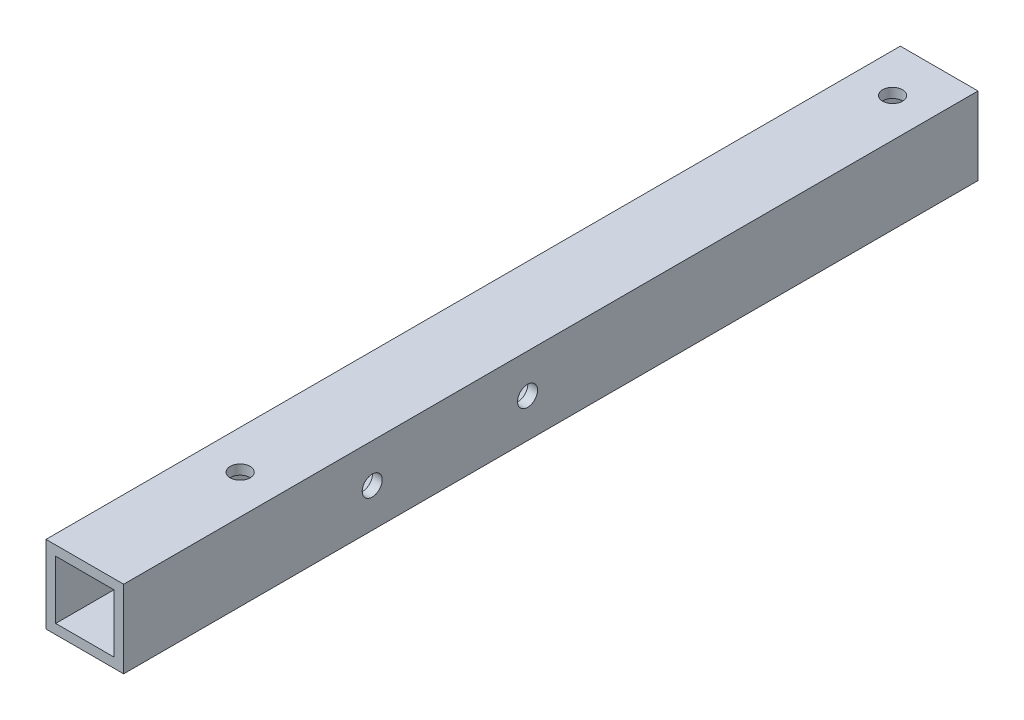
SolidWorks part; units mm, degrees
material "1060 Alloy"
ref_plane "Front Plane" through (0, 0, 0) normal (0, 0, 1) x (1, 0, 0)
ref_plane "Top Plane" through (0, 0, 0) normal (0, 1, 0) x (1, 0, 0)
ref_plane "Right Plane" through (0, 0, 0) normal (1, 0, 0) x (0, 0, -1)
sketch "Sketch2" plane through (0, 0, 0) normal (0, 0, 1) x (1, 0, 0)
  line L1 (12.7, -12.7) -> (-12.7, -12.7)
  line L2 (12.7, -12.7) -> (12.7, 12.7)
  line L3 (12.7, 12.7) -> (-12.7, 12.7)
  line L4 (-12.7, -12.7) -> (-12.7, 12.7)
  line L5 (12.7, -12.7) -> (-12.7, 12.7) construction
  line L6 (12.7, 12.7) -> (-12.7, -12.7) construction
  point P0 (0, 0)
  dimension "D1" = 25.4
extrude "Boss-Extrude1" add sketch "Sketch2" along normal blind 279.4 contours L4 L3 L2 L1
sketch "Sketch4" plane through (0, 0, 0) normal (0, 0, 1) x (1, 0, 0)
  line L0 (12.7, -12.7) -> (12.7, 12.7) construction
  line L1 (-9.525, -9.525) -> (9.525, -9.525)
  line L2 (-9.525, -9.525) -> (-9.525, 9.525)
  line L3 (-9.525, 9.525) -> (9.525, 9.525)
  line L4 (9.525, -9.525) -> (9.525, 9.525)
  line L5 (-9.525, -9.525) -> (9.525, 9.525) construction
  line L6 (-9.525, 9.525) -> (9.525, -9.525) construction
  line L7 (12.7, 12.7) -> (-12.7, 12.7) construction
  point P0 (0, 0)
  dimension "D1" = 3.175
  dimension "D2" = 3.175
extrude "Cut-Extrude1" cut sketch "Sketch4" along normal through all
sketch "Sketch5" plane through (0, 12.7, 0) normal (0, 1, 0) x (1, 0, 0)
  line L0 (12.7, 0) -> (-12.7, 0) construction
  circle A0 centre (0, -15.24) radius 3.2639
  point P5 (0, 0)
  dimension "D1" = 6.5278
  dimension "D2" = 15.24
extrude "Cut-Extrude2" cut sketch "Sketch5" against normal through all
sketch "Sketch6" plane through (0, 12.7, 0) normal (0, 1, 0) x (1, 0, 0)
  line L0 (12.7, -279.4) -> (-12.7, -279.4) construction
  line L1 (12.7, 0) -> (-12.7, 0) construction
  circle A0 centre (0, -228.6) radius 3.2639
  point P4 (0, -279.4)
  dimension "D1" = 6.5278
  dimension "D2" = 228.6
extrude "Cut-Extrude3" cut sketch "Sketch6" against normal through all
sketch "Sketch8" plane through (-12.7, 0, 0) normal (-1, 0, 0) x (0, 0, 1)
  line L0 (0, -12.7) -> (0, 12.7) construction
  line L1 (279.4, -12.7) -> (279.4, 12.7) construction
  circle A0 centre (198.12, 0) radius 3.2639
  circle A1 centre (147.32, 0) radius 3.2639
  point P8 (279.4, 0)
  dimension "D1" = 6.5278
  dimension "D2" = 147.32
  dimension "D3" = 198.12
extrude "Cut-Extrude5" cut sketch "Sketch8" against normal through all
